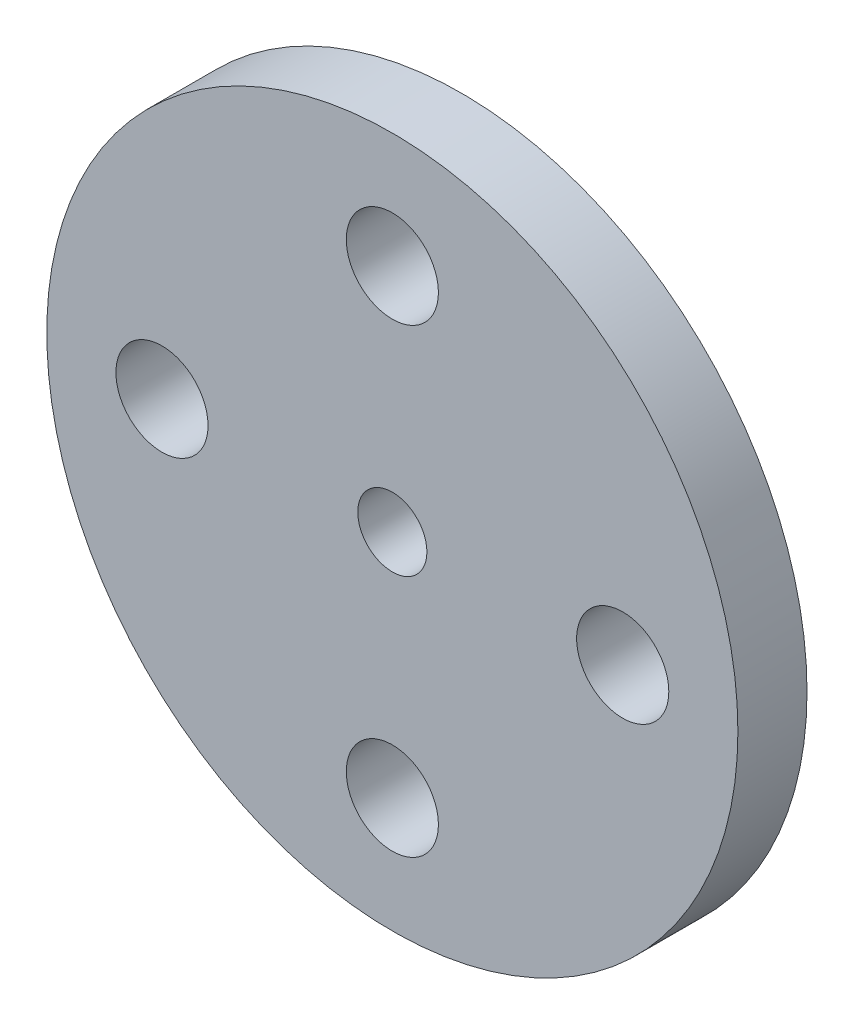
SolidWorks part; units mm, degrees
ref_plane "Front" through (0, 0, 0) normal (0, 0, 1) x (1, 0, 0)
ref_plane "Top" through (0, 0, 0) normal (0, 1, 0) x (1, 0, 0)
ref_plane "Right" through (0, 0, 0) normal (1, 0, 0) x (0, 0, -1)
sketch "草图1" plane through (0, 0, 0) normal (0, 0, 1) x (1, 0, 0)
  circle A0 centre (0, 0) radius 3.5
  circle A1 centre (0, 0) radius 4.5
extrude "凸台-拉伸1" add sketch "草图1" along normal blind 5
sketch "草图2" plane through (0, 0, 5) normal (0, 0, 1) x (1, 0, 0)
  circle A0 centre (0, 0) radius 15
  circle A1 centre (0, 0) radius 1.5
  circle A2 centre (0, 0) radius 10 construction
  circle A3 centre (0, 10) radius 2
  circle A4 centre (10, 0) radius 2
  circle A5 centre (0, -10) radius 2
  circle A6 centre (-10, 0) radius 2
  point P16 (0, 0)
  dimension "D1" = 4
extrude "凸台-拉伸2" add sketch "草图2" along normal blind 3
